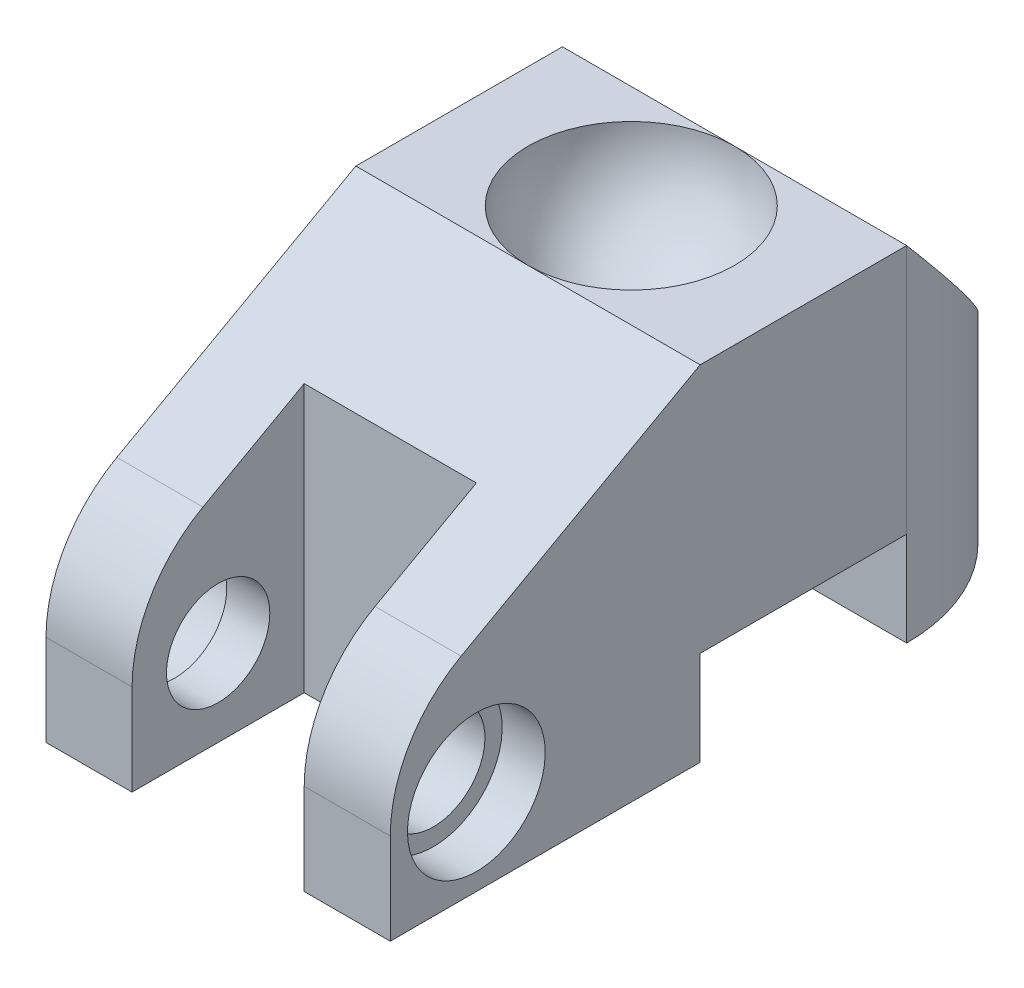
SolidWorks part; units mm, degrees
ref_plane "Front Plane" through (0, 0, 0) normal (0, 0, 1) x (1, 0, 0)
ref_plane "Top Plane" through (0, 0, 0) normal (0, 1, 0) x (1, 0, 0)
ref_plane "Right Plane" through (0, 0, 0) normal (1, 0, 0) x (0, 0, -1)
sketch "Sketch5" plane through (0, 0, 0) normal (0, 0, 1) x (1, 0, 0)
  line L1 (-9.2175, 9.0395) -> (10.7825, 9.0395)
  line L2 (-9.2175, 9.0395) -> (-9.2175, -10.9605)
  line L3 (-9.2175, -10.9605) -> (10.7825, -10.9605)
  line L4 (10.7825, 9.0395) -> (10.7825, -10.9605)
  dimension "D1" = 20
  dimension "D2" = 20
extrude "Boss-Extrude1" add sketch "Sketch5" along normal blind 40 contours L2 L1 L4 L3
sketch "Sketch7" plane through (10.7825, 0, 0) normal (1, 0, 0) x (0, 0, -1)
  line L0 (-40, -10.9605) -> (0, -10.9605) construction
  line L5 (-40, 9.0395) -> (-40, -10.9605) construction
  line L10 (-10, -5.4803) -> (-10, -10.9605)
  line L11 (-10, 9.0395) -> (-22, 9.0395)
  line L15 (-22, -5.4803) -> (-22, -10.9605)
  line L16 (-22, -5.4803) -> (-10, -5.4803)
  line L17 (-10, -5.4803) -> (-10, -10.9605)
  line L18 (-22, 9.0395) -> (-40, -0.9605)
  line L19 (-10, -5.4803) -> (-10, -10.9605)
  line L20 (-22, -5.4803) -> (-22, -10.9605)
  line L21 (0, -2.7401) -> (-10, 9.0395)
  line L22 (-40, -0.9605) -> (-40, 9.0395)
  line L23 (-40, 9.0395) -> (0, 9.0395) construction
  line L24 (-40, 9.0395) -> (-22, 9.0395)
  line L25 (-10, 9.0395) -> (0, 9.0395)
  line L26 (0, 9.0395) -> (0, -2.7401)
  line L27 (-22, -10.9605) -> (-10, -10.9605)
  line L28 (-51.1595, -1.3644) -> (-51.117, -1.3644)
  line M3 (0, -10.9605) -> (0, 9.0395)
  line M4 (0, 9.0395) -> (-40, 9.0395)
  line M5 (-40, 9.0395) -> (-40, -10.9605)
  line M6 (-40, -10.9605) -> (0, -10.9605)
  dimension "D1" = 10
  dimension "D2" = 12
extrude "Cut-Extrude3" cut sketch "Sketch7" against normal blind 20 contours L18 M4 M5 | L16 L15 L10 M6 | L21 M3 M4
sketch "Sketch8" plane through (0, -10.9605, 0) normal (0, -1, 0) x (1, 0, 0)
  line L0 (10.7825, 10) -> (10.7825, 0)
  line L1 (-9.2175, 10) -> (10.7825, 10) construction
  line L3 (-9.2175, 10) -> (-9.2175, 0)
  line L4 (-9.2175, 0) -> (10.7825, 0)
  line L5 (10.7825, 0) -> (10.7825, 10)
  line L7 (-9.2175, 40) -> (10.7825, 40) construction
  line L10 (-4.2175, 40) -> (5.7825, 40)
  line L11 (-4.2175, 30) -> (-4.2175, 40)
  line L12 (-4.2175, 40) -> (5.7825, 40)
  line L13 (5.7825, 40) -> (5.7825, 30)
  line L14 (-4.2175, 40) -> (-4.2175, 30)
  line L15 (-4.2175, 30) -> (5.7825, 30)
  line L16 (5.7825, 40) -> (5.7825, 30)
  line L17 (-9.2175, 0) -> (-9.2175, 10)
  arc A1 (-9.2175, 10) -> (10.7825, 10) centre (0.7825, 10) ccw
  line M2 (-9.2175, 10) -> (-9.2175, 0)
  line M3 (-9.2175, 0) -> (10.7825, 0)
  line M4 (10.7825, 0) -> (10.7825, 10)
  dimension "D1" = 10
extrude "Cut-Extrude5" cut sketch "Sketch8" against normal blind 20 contours A1 M2 M3 | A1 L4 M4 | L11 L15 L13 L10
sketch "Sketch10" plane through (0, 9.0395, 0) normal (0, 1, 0) x (1, 0, 0)
  line L1 (-5.2175, -16) -> (6.7825, -16)
  arc A0 (-5.2175, -16) -> (6.7825, -16) centre (0.7825, -16) ccw
  dimension "D1" = 12
revolve "Cut-Revolve2" cut sketch "Sketch10" angle 360 about L1
sketch "Sketch12" plane through (10.7825, 0, 0) normal (1, 0, 0) x (0, 0, -1)
  line L0 (-40, -0.9605) -> (-40, -10.9605) construction
  line L1 (-40, -10.9605) -> (-22, -10.9605) construction
  circle A0 centre (-35, -5.9605) radius 3
  dimension "D2" = 5
  dimension "D1" = 5
extrude "Cut-Extrude9" cut sketch "Sketch12" against normal blind 20 contours A0
sketch "Sketch16" plane through (10.7825, 0, 0) normal (1, 0, 0) x (0, 0, -1)
  circle A0 centre (-35, -5.9605) radius 4
  circle A1 centre (-35, -5.9605) radius 3 construction
  dimension "D1" = 0
extrude "Cut-Extrude10" cut sketch "Sketch16" against normal blind 2.5
sketch "Sketch17" plane through (-9.2175, 0, 0) normal (-1, 0, 0) x (0, 0, 1)
  circle A0 centre (35, -5.9605) radius 4
  circle A1 centre (35, -5.9605) radius 3 construction
  dimension "D1" = 0
extrude "Cut-Extrude11" cut sketch "Sketch17" against normal blind 2.5
fillet "Fillet8" radius 8 2 edges at (-6.7175, -0.9605, 40) (8.2825, -0.9605, 40)
sketch "Sketch18" plane through (0, -5.4803, 0) normal (0, -1, 0) x (-1, 0, 0)
  circle A1 centre (-0.7825, -16) radius 6.0236
extrude "Boss-Extrude2" add sketch "Sketch18" along normal blind 3
sketch "Sketch19" plane through (0, -8.4803, 0) normal (0, -1, 0) x (-1, 0, 0)
  circle A0 centre (-0.7825, -16) radius 4
  dimension "D1" = 8
extrude "Cut-Extrude12" cut sketch "Sketch19" against normal blind 10
